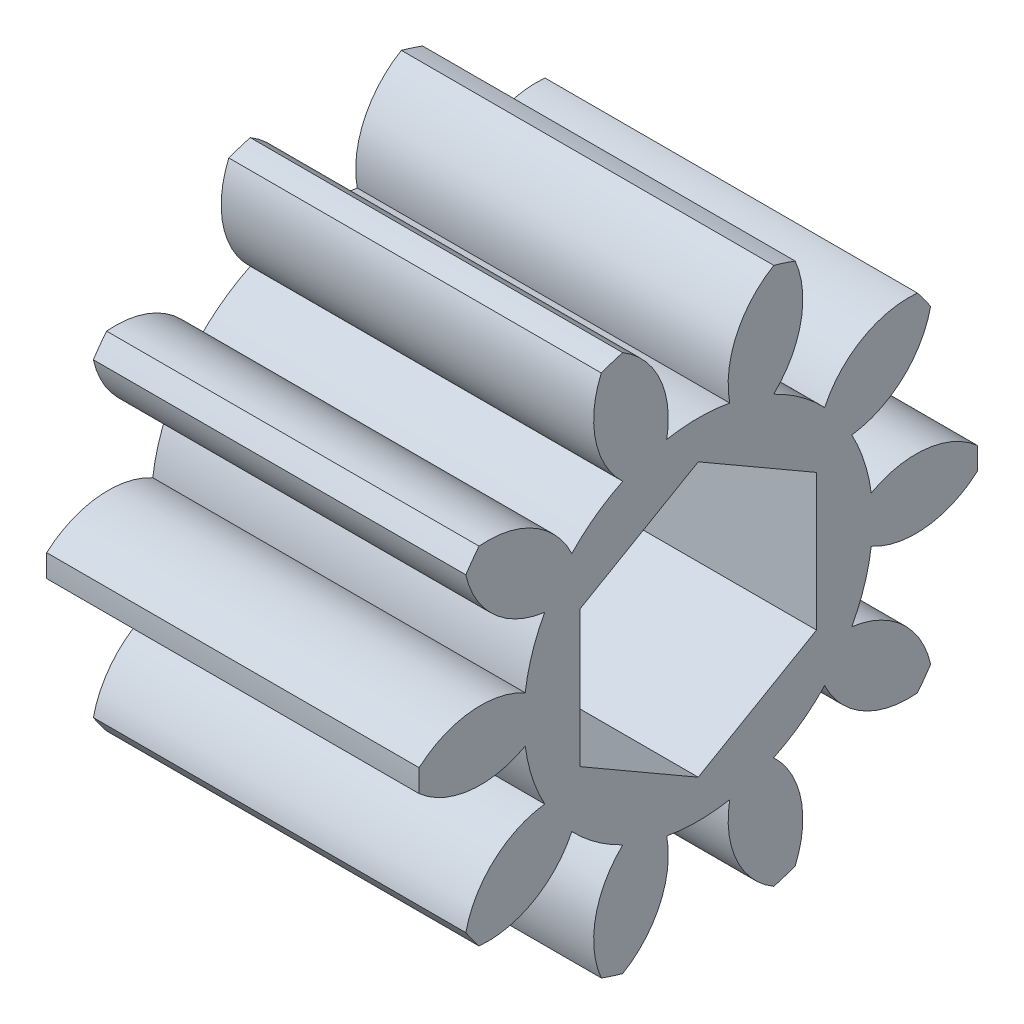
SolidWorks part; units mm, degrees
ref_plane "Plane1" through (0, 0, 0) normal (0, 0, 1) x (1, 0, 0)
ref_plane "Plane2" through (0, 0, 0) normal (0, 1, 0) x (1, 0, 0)
ref_plane "Plane3" through (0, 0, 0) normal (1, 0, 0) x (0, 0, -1)
other "Configuration Table"
sketch "HoldingSke" plane through (0, 0, 0) normal (0, 1, 0) x (1, 0, 0)
  line L0 (0, 0) -> (0.3939, -0.0695)
  line L1 (-15, 0) -> (100, 0) construction
  line L2 (0, 0) -> (-2.1039, 2.3779)
  line L3 (0, 0) -> (-11.863, 4.5341)
  line L4 (0, 0) -> (8.5048, 1.4996)
  line L5 (0, 0) -> (-46.8476, -17.4728)
  line L6 (0, 0) -> (-11.6055, -7.8303)
  line L7 (-2.1039, 2.3779) -> (8.6587, 51.2064)
  line L8 (-76.2, 54.61) -> (-74.4, 54.61)
  line L9 (-67.7845, 28.3722) -> (-49.3413, 33.142)
  line L10 (-76.2, 71.12) -> (104.1128, 71.12)
  line L11 (0, 0) -> (-14, 0)
  line L12 (-76.2, 101.6) -> (-76.113, 101.6)
  line L13 (24.9733, 27.94) -> (52.9518, 28.4284)
  line L14 (24.9733, 27.94) -> (24.9743, 27.94)
  line L15 (24.9733, 27.94) -> (100.4006, 29.5858)
  line L16 (-63.627, -2.5) -> (-12.827, -2.5)
  circle A0 centre (0, 0) radius 5
  circle A1 centre (0, 0) radius 9.374
  circle A2 centre (0, 0) radius 37.5
  circle A3 centre (0, 0) radius 5
  dimension "MHD" = 18.748
  dimension "Hub_dia" = 75
  dimension "Bore" = 10
  dimension "MBD" = 10
  dimension "Num_teeth" = 10
  dimension "Pitch" = 0.4
  dimension "Overall_len" = 50
  dimension "Show_teeth" = 10
  dimension "Thickness" = 14
  dimension "OAL" = 50.0006
  dimension "T_dim" = 1.8
  dimension "Ap" = 14.5
  dimension "H" = 19.05
  dimension "Pitch_radius" = 180.3128
  dimension "Width" = 14
  dimension "Backlash" = 0.087
  dimension "Addendum_fac" = 1
  dimension "Dedendum_fac" = 1.25
  dimension "Clearance_fac" = 0.25
  dimension "Dedendum_add" = 0.001
  dimension "Module" = 2.5
sketch "BasProSke" plane through (0, 0, 0) normal (0, 1, 0) x (1, 0, 0)
  line L0 (-10, 0) -> (60, 0) construction
  line L1 (0, 0) -> (0, 15)
  line L2 (0, 0) -> (14, 0)
  line L3 (14, 0) -> (14, 15)
  line L4 (14, 15) -> (0, 15)
  dimension "Thickness" = 14
  dimension "Diameter" = 30
revolve "Base-Revolve" add sketch "BasProSke" angle 360 about L0
sketch "TooCutSke" plane through (0, 0, 0) normal (1, 0, 0) x (0, 0, -1)
  line L1 (0, 0) -> (0, 107) construction
  line L2 (0, 0) -> (-2.1074, 12.3211) construction
  line L3 (0, 0) -> (-7.6446, 23.5277) construction
  line L4 (-2.1074, 12.3211) -> (-3.8223, 11.7639) construction
  arc A0 (1.6916, 9.2201) -> (-1.6916, 9.2201) centre (0, 0) ccw
  arc A1 (4.0875, 14.4587) -> (-4.0875, 14.4587) centre (0, 0) ccw
  circle A2 centre (0, 0) radius 12.5 construction
  circle A3 centre (0, 0) radius 12.1018 construction
  arc A4 (-1.6916, 9.2201) -> (-4.0875, 14.4587) centre (-6.6064, 10.1395) ccw
  arc A5 (4.0875, 14.4587) -> (1.6916, 9.2201) centre (6.6064, 10.1395) ccw
  dimension "Root_dia" = 18.748
  dimension "Overcut_dia" = 30.0508
  dimension "Pitch_dia" = 25
  dimension "Base_dia" = 24.2037
  dimension "Flank_rad" = 5
  dimension "Half_ang" = 18
  dimension "Half_CT" = 1.8032
extrude "ToothCut" cut sketch "TooCutSke" along normal through all
fillet "Breaks" [suppressed] radius 0.05
fillet "RootFillets" [suppressed] radius 0.626
pattern_circular "TeethCuts" count 10 every 36 about axis through (-10, 0, 0) along (1, 0, 0) of "ToothCut", "RootFillets", "Breaks"
sketch "HubNeaOneSke" plane through (0, 0, 0) normal (-1, 0, 0) x (0, 0, 1)
  circle A0 centre (0, 0) radius 9.374
  dimension "Diameter" = 18.748
extrude "HubNearOne" [suppressed] add sketch "HubNeaOneSke" along normal blind 36.0006
sketch "HubNeaBotSke" plane through (0, 0, 0) normal (-1, 0, 0) x (0, 0, 1)
  circle A0 centre (0, 0) radius 9.374
  dimension "Diameter" = 18.748
extrude "HubNearBoth" [suppressed] add sketch "HubNeaBotSke" along normal blind 18.0003
ref_plane "FarPln" through (14, 0, 0) normal (1, 0, 0) x (0, 0, -1)
sketch "HubFarSke" plane through (14, 0, 0) normal (1, 0, 0) x (0, 0, -1)
  circle A0 centre (0, 0) radius 9.374
  dimension "Diameter" = 18.748
extrude "HubFar" [suppressed] add sketch "HubFarSke" along normal blind 18.0003
sketch "BorSke" plane through (0, 0, 0) normal (1, 0, 0) x (0, 0, -1)
  circle A0 centre (0, 0) radius 5
  dimension "Diameter" = 10
extrude "Bore" cut sketch "BorSke" along normal mid plane 100.0011
sketch "KeySke" plane through (0, 0, 0) normal (1, 0, 0) x (0, 0, -1)
  line L0 (-2, 0) -> (-2, 6.8)
  line L1 (-2, 6.8) -> (2, 6.8)
  line L2 (2, 6.8) -> (2, 0)
  line L3 (0, 0) -> (0, 34) construction
  line L4 (-2, 0) -> (2, 0)
  dimension "Offset" = 6.8
  dimension "Width" = 4
extrude "Keyway" [suppressed] cut sketch "KeySke" along normal mid plane 100.0011
pattern_circular "Keyway2" [suppressed] count 2 every 90 about axis through (-10, 0, 0) along (1, 0, 0)
sketch "Sketch1" plane through (14, 0, 0) normal (1, 0, 0) x (0, 0, -1)
  line L1 (0, -7.3323) -> (6.35, -3.6662)
  line L2 (6.35, -3.6662) -> (6.35, 3.6662)
  line L3 (6.35, 3.6662) -> (0, 7.3323)
  line L4 (0, 7.3323) -> (-6.35, 3.6662)
  line L5 (-6.35, 3.6662) -> (-6.35, -3.6662)
  line L6 (-6.35, -3.6662) -> (0, -7.3323)
  circle A0 centre (0, 0) radius 6.35 construction
  point P1 (2.938, 6.4082)
  point P9 (0, 0)
  point P10 (0, 0)
  point P12 (0, 7.5633)
  dimension "D1" = 12.7
extrude "Cut-Extrude1" cut sketch "Sketch1" against normal through all
sketch "Sketch2" plane through (14, 0, 0) normal (1, 0, 0) x (0, 0, -1)
  line L0 (-6.35, -3.6662) -> (0, -7.3323)
  line L1 (-6.35, -3.6662) -> (0, -7.3323)
  line L2 (0, -7.3323) -> (6.35, -3.6662)
  line L3 (0, -7.3323) -> (6.35, -3.6662)
  line L4 (6.35, -3.6662) -> (6.35, 3.6662)
  line L5 (6.35, -3.6662) -> (6.35, 3.6662)
  line L6 (6.35, 3.6662) -> (0, 7.3323)
  line L7 (6.35, 3.6662) -> (0, 7.3323)
  line L8 (0, 7.3323) -> (-6.35, 3.6662)
  line L9 (0, 7.3323) -> (-6.35, 3.6662)
  line L10 (-6.35, 3.6662) -> (-6.35, -3.6662)
  line L11 (-6.35, 3.6662) -> (-6.35, -3.6662)
  arc A0 (14.9878, -0.6039) -> (14.9878, 0.6039) centre (0, 0) ccw
  arc A1 (14.9878, -0.6039) -> (14.9878, 0.6039) centre (0, 0) ccw
  arc A2 (9.2916, -1.2403) -> (14.9878, -0.6039) centre (11.6848, 3.1497) ccw
  arc A3 (9.2916, -1.2403) -> (14.9878, -0.6039) centre (11.6848, 3.1497) ccw
  arc A4 (8.2461, -4.458) -> (9.2916, -1.2403) centre (0, 0) ccw
  arc A5 (8.2461, -4.458) -> (9.2916, -1.2403) centre (0, 0) ccw
  arc A6 (12.4804, -8.3211) -> (8.2461, -4.458) centre (7.6018, -9.4163) ccw
  arc A7 (12.4804, -8.3211) -> (8.2461, -4.458) centre (7.6018, -9.4163) ccw
  arc A8 (11.7705, -9.2982) -> (12.4804, -8.3211) centre (0, 0) ccw
  arc A9 (11.7705, -9.2982) -> (12.4804, -8.3211) centre (0, 0) ccw
  arc A10 (6.788, -6.4649) -> (11.7705, -9.2982) centre (11.3045, -4.3199) ccw
  arc A11 (6.788, -6.4649) -> (11.7705, -9.2982) centre (11.3045, -4.3199) ccw
  arc A12 (4.0509, -8.4535) -> (6.788, -6.4649) centre (0, 0) ccw
  arc A13 (4.0509, -8.4535) -> (6.788, -6.4649) centre (0, 0) ccw
  arc A14 (5.2058, -14.0677) -> (4.0509, -8.4535) centre (0.6152, -12.0862) ccw
  arc A15 (5.2058, -14.0677) -> (4.0509, -8.4535) centre (0.6152, -12.0862) ccw
  arc A16 (4.0572, -14.4409) -> (5.2058, -14.0677) centre (0, 0) ccw
  arc A17 (4.0572, -14.4409) -> (5.2058, -14.0677) centre (0, 0) ccw
  arc A18 (1.6916, -9.2201) -> (4.0572, -14.4409) centre (6.6064, -10.1395) ccw
  arc A19 (1.6916, -9.2201) -> (4.0572, -14.4409) centre (6.6064, -10.1395) ccw
  arc A20 (-1.6916, -9.2201) -> (1.6916, -9.2201) centre (0, 0) ccw
  arc A21 (-1.6916, -9.2201) -> (1.6916, -9.2201) centre (0, 0) ccw
  arc A22 (-4.0572, -14.4409) -> (-1.6916, -9.2201) centre (-6.6064, -10.1395) ccw
  arc A23 (-4.0572, -14.4409) -> (-1.6916, -9.2201) centre (-6.6064, -10.1395) ccw
  arc A24 (-5.2058, -14.0677) -> (-4.0572, -14.4409) centre (0, 0) ccw
  arc A25 (-5.2058, -14.0677) -> (-4.0572, -14.4409) centre (0, 0) ccw
  arc A26 (-4.0509, -8.4535) -> (-5.2058, -14.0677) centre (-0.6152, -12.0862) ccw
  arc A27 (-4.0509, -8.4535) -> (-5.2058, -14.0677) centre (-0.6152, -12.0862) ccw
  arc A28 (-6.788, -6.4649) -> (-4.0509, -8.4535) centre (0, 0) ccw
  arc A29 (-6.788, -6.4649) -> (-4.0509, -8.4535) centre (0, 0) ccw
  arc A30 (-11.7705, -9.2982) -> (-6.788, -6.4649) centre (-11.3045, -4.3199) ccw
  arc A31 (-11.7705, -9.2982) -> (-6.788, -6.4649) centre (-11.3045, -4.3199) ccw
  arc A32 (-12.4804, -8.3211) -> (-11.7705, -9.2982) centre (0, 0) ccw
  arc A33 (-12.4804, -8.3211) -> (-11.7705, -9.2982) centre (0, 0) ccw
  arc A34 (-8.2461, -4.458) -> (-12.4804, -8.3211) centre (-7.6018, -9.4163) ccw
  arc A35 (-8.2461, -4.458) -> (-12.4804, -8.3211) centre (-7.6018, -9.4163) ccw
  arc A36 (-9.2916, -1.2403) -> (-8.2461, -4.458) centre (0, 0) ccw
  arc A37 (-9.2916, -1.2403) -> (-8.2461, -4.458) centre (0, 0) ccw
  arc A38 (-14.9878, -0.6039) -> (-9.2916, -1.2403) centre (-11.6848, 3.1497) ccw
  arc A39 (-14.9878, -0.6039) -> (-9.2916, -1.2403) centre (-11.6848, 3.1497) ccw
  arc A40 (-14.9878, 0.6039) -> (-14.9878, -0.6039) centre (0, 0) ccw
  arc A41 (-14.9878, 0.6039) -> (-14.9878, -0.6039) centre (0, 0) ccw
  arc A42 (-9.2916, 1.2403) -> (-14.9878, 0.6039) centre (-11.6848, -3.1497) ccw
  arc A43 (-9.2916, 1.2403) -> (-14.9878, 0.6039) centre (-11.6848, -3.1497) ccw
  arc A44 (-8.2461, 4.458) -> (-9.2916, 1.2403) centre (0, 0) ccw
  arc A45 (-8.2461, 4.458) -> (-9.2916, 1.2403) centre (0, 0) ccw
  arc A46 (-12.4804, 8.3211) -> (-8.2461, 4.458) centre (-7.6018, 9.4163) ccw
  arc A47 (-12.4804, 8.3211) -> (-8.2461, 4.458) centre (-7.6018, 9.4163) ccw
  arc A48 (-11.7705, 9.2982) -> (-12.4804, 8.3211) centre (0, 0) ccw
  arc A49 (-11.7705, 9.2982) -> (-12.4804, 8.3211) centre (0, 0) ccw
  arc A50 (-6.788, 6.4649) -> (-11.7705, 9.2982) centre (-11.3045, 4.3199) ccw
  arc A51 (-6.788, 6.4649) -> (-11.7705, 9.2982) centre (-11.3045, 4.3199) ccw
  arc A52 (-4.0509, 8.4535) -> (-6.788, 6.4649) centre (0, 0) ccw
  arc A53 (-4.0509, 8.4535) -> (-6.788, 6.4649) centre (0, 0) ccw
  arc A54 (-5.2058, 14.0677) -> (-4.0509, 8.4535) centre (-0.6152, 12.0862) ccw
  arc A55 (-5.2058, 14.0677) -> (-4.0509, 8.4535) centre (-0.6152, 12.0862) ccw
  arc A56 (-4.0572, 14.4409) -> (-5.2058, 14.0677) centre (0, 0) ccw
  arc A57 (-4.0572, 14.4409) -> (-5.2058, 14.0677) centre (0, 0) ccw
  arc A58 (-1.6916, 9.2201) -> (-4.0572, 14.4409) centre (-6.6064, 10.1395) ccw
  arc A59 (-1.6916, 9.2201) -> (-4.0572, 14.4409) centre (-6.6064, 10.1395) ccw
  arc A60 (1.6916, 9.2201) -> (-1.6916, 9.2201) centre (0, 0) ccw
  arc A61 (1.6916, 9.2201) -> (-1.6916, 9.2201) centre (0, 0) ccw
  arc A62 (4.0572, 14.4409) -> (1.6916, 9.2201) centre (6.6064, 10.1395) ccw
  arc A63 (4.0572, 14.4409) -> (1.6916, 9.2201) centre (6.6064, 10.1395) ccw
  arc A64 (5.2058, 14.0677) -> (4.0572, 14.4409) centre (0, 0) ccw
  arc A65 (5.2058, 14.0677) -> (4.0572, 14.4409) centre (0, 0) ccw
  arc A66 (4.0509, 8.4535) -> (5.2058, 14.0677) centre (0.6152, 12.0862) ccw
  arc A67 (4.0509, 8.4535) -> (5.2058, 14.0677) centre (0.6152, 12.0862) ccw
  arc A68 (6.788, 6.4649) -> (4.0509, 8.4535) centre (0, 0) ccw
  arc A69 (6.788, 6.4649) -> (4.0509, 8.4535) centre (0, 0) ccw
  arc A70 (11.7705, 9.2982) -> (6.788, 6.4649) centre (11.3045, 4.3199) ccw
  arc A71 (11.7705, 9.2982) -> (6.788, 6.4649) centre (11.3045, 4.3199) ccw
  arc A72 (12.4804, 8.3211) -> (11.7705, 9.2982) centre (0, 0) ccw
  arc A73 (12.4804, 8.3211) -> (11.7705, 9.2982) centre (0, 0) ccw
  arc A74 (8.2461, 4.458) -> (12.4804, 8.3211) centre (7.6018, 9.4163) ccw
  arc A75 (8.2461, 4.458) -> (12.4804, 8.3211) centre (7.6018, 9.4163) ccw
  arc A76 (9.2916, 1.2403) -> (8.2461, 4.458) centre (0, 0) ccw
  arc A77 (9.2916, 1.2403) -> (8.2461, 4.458) centre (0, 0) ccw
  arc A78 (14.9878, 0.6039) -> (9.2916, 1.2403) centre (11.6848, -3.1497) ccw
  arc A79 (14.9878, 0.6039) -> (9.2916, 1.2403) centre (11.6848, -3.1497) ccw
extrude "Boss-Extrude1" add sketch "Sketch2" along normal blind 6
equation "' \"Module@HoldingSke\" = 6.35"
equation "' \"Num_teeth@HoldingSke\" = 12"
equation "' \"Ap@HoldingSke\" =  20"
equation "' \"Ap@HoldingSke\" = 20"
equation "' \"Width@HoldingSke\" = 0.5 * 25.4"
equation "' \"Hub_dia@HoldingSke\"= 1 * 25.4"
equation "' \"Hub_dia@HoldingSke\" = 1 * 25.4"
equation "' \"Overall_len@HoldingSke\" = 1.0 * 25.4"
equation "' \"Bore@HoldingSke\" = 0.75 * 25.4"
equation "' \"T_dim@HoldingSke\" = 0.1 * 25.4"
equation "' \"Width@KeySke\" = 0.25 * 25.4"
equation "' \"Show_teeth@HoldingSke\" = 13"
equation "' \"Backlash@HoldingSke\" = 0.009 * 25.4"
equation "' \"Addendum_fac@HoldingSke\" = 1.0"
equation "' \"Dedendum_fac@HoldingSke\" = 1.25"
equation "' \"Dedendum_add@HoldingSke\" = 0.00005 * 25.4"
equation "' \"Clearance_fac@HoldingSke\" = 0.25"
equation "\"Pitch@HoldingSke\" = 1 / \"Module@HoldingSke\""
equation "\"Overcut_dia@TooCutSke\" = (\"Num_teeth@HoldingSke\" + 2 * \"Addendum_fac@HoldingSke\") / \"Pitch@HoldingSke\" + 0.002 * 25.4"
equation "\"Pitch_dia@TooCutSke\" = \"Num_teeth@HoldingSke\" / \"Pitch@HoldingSke\""
equation "\"Base_dia@TooCutSke\" = \"Num_teeth@HoldingSke\" / \"Pitch@HoldingSke\" * cos((\"Ap@HoldingSke\"  * 3.14159265 / 180))"
equation "\"Root_dia@TooCutSke\" = (\"Num_teeth@HoldingSke\" + 2) / \"Pitch@HoldingSke\" - 2 * (\"Addendum_fac@HoldingSke\" + \"Dedendum_fac@HoldingSke\") / \"Pitch@HoldingSke\" - \"Dedendum_add@HoldingSke\" * 2"
equation "\"Half_ang@TooCutSke\" = 180 / \"Num_teeth@HoldingSke\""
equation "\"Half_CT@TooCutSke\" = \"Num_teeth@HoldingSke\" / \"Pitch@HoldingSke\" * sin((3.14159265 / 2 / \"Num_teeth@HoldingSke\")) / 2 - 7 * \"Backlash@HoldingSke\" / 4"
equation "\"Flank_rad@TooCutSke\" = \"Num_teeth@HoldingSke\" / \"Pitch@HoldingSke\" / 5"
equation "\"Radius@RootFillets\" = \"Clearance_fac@HoldingSke\" / \"Pitch@HoldingSke\" + \"Dedendum_add@HoldingSke\""
equation "\"Break_rad@Breaks\" = 0.02 / \"Pitch@HoldingSke\""
equation "\"Thickness@HoldingSke\" = \"Width@HoldingSke\""
equation "\"OAL@HoldingSke\" = \"Thickness@HoldingSke\""
equation "\"MHD@HoldingSke\" = (\"Num_teeth@HoldingSke\" + 2) / \"Pitch@HoldingSke\" - 2 * (\"Addendum_fac@HoldingSke\" + \"Dedendum_fac@HoldingSke\")  / \"Pitch@HoldingSke\" - \"Dedendum_add@HoldingSke\" * 2"
equation "\"MBD@HoldingSke\" = (\"Num_teeth@HoldingSke\" + 2) / \"Pitch@HoldingSke\" - 2 * (\"Addendum_fac@HoldingSke\" + \"Dedendum_fac@HoldingSke\")  / \"Pitch@HoldingSke\" - \"Dedendum_add@HoldingSke\" * 2 - 0.002 * 25.4"
equation "\"MHD@HoldingSke\" = ((sgn( \"MHD@HoldingSke\" - \"Hub_dia@HoldingSke\" )-1)*( \"MHD@HoldingSke\" - \"Hub_dia@HoldingSke\" ))/-2+ \"Hub_dia@HoldingSke\""
equation "\"MBD@HoldingSke\" = ((sgn( \"MBD@HoldingSke\" - \"Bore@HoldingSke\" )-1)*( \"MBD@HoldingSke\" - \"Bore@HoldingSke\" ))/-2+ \"Bore@HoldingSke\""
equation "\"OAL@HoldingSke\" = ((sgn( \"OAL@HoldingSke\" - \"Overall_len@HoldingSke\" )+1)*( \"OAL@HoldingSke\" - \"Overall_len@HoldingSke\" ))/2 + \"Overall_len@HoldingSke\" + 0.000002 * 25.4"
equation "\"Num_teeth@TeethCuts\" = int( \"Show_teeth@HoldingSke\" ) + 1"
equation "\"Num_teeth@TeethCuts\" = ((sgn( \"Num_teeth@TeethCuts\" - \"Num_teeth@HoldingSke\" )-1)*( \"Num_teeth@TeethCuts\" - \"Num_teeth@HoldingSke\" ))/-2+ \"Num_teeth@HoldingSke\""
equation "\"Num_teeth@TeethCuts\" = ((sgn( \"Num_teeth@TeethCuts\" - 2.0)+1)*( \"Num_teeth@TeethCuts\" - 2.0))/2 +2.0"
equation "\"Angle@TeethCuts\" = 360.0 / \"Num_teeth@HoldingSke\""
equation "\"Diameter@BasProSke\" = (\"Num_teeth@HoldingSke\" + 2 * \"Addendum_fac@HoldingSke\") / \"Pitch@HoldingSke\""
equation "\"Thickness@BasProSke\"  = \"Thickness@HoldingSke\""
equation "' \"Fillet_rad@BasProSke\" =  \"Thickness@HoldingSke\" * 0.05"
equation "' \"Fillet_rad@BasProSke\" = \"Thickness@HoldingSke\" * 0.05"
equation "\"MHD@HoldingSke\" = ((sgn( \"MHD@HoldingSke\" - \"Root_dia@TooCutSke\" )-1)*( \"MHD@HoldingSke\" - \"Root_dia@TooCutSke\" ))/-2+ \"Root_dia@TooCutSke\""
equation "\"Diameter@HubNeaOneSke\" = \"MHD@HoldingSke\""
equation "\"Length@HubNearOne\" = \"OAL@HoldingSke\" - \"Thickness@BasProSke\""
equation "\"Diameter@HubNeaBotSke\" = \"MHD@HoldingSke\""
equation "\"Length@HubNearBoth\" = ( \"OAL@HoldingSke\" - \"Thickness@BasProSke\" ) / 2.0"
equation "\"Thickness@FarPln\" = \"Thickness@BasProSke\""
equation "\"Diameter@HubFarSke\" = \"MHD@HoldingSke\""
equation "\"Length@HubFar\" = ( \"OAL@HoldingSke\" - \"Thickness@BasProSke\" ) / 2.0"
equation "\"Diameter@BorSke\" = \"MBD@HoldingSke\""
equation "\"D1@Bore\" = \"OAL@HoldingSke\" * 2.0"
equation "\"D1@Keyway\" = \"OAL@HoldingSke\" * 2.0"
equation "\"Offset@KeySke\" = \"T_dim@HoldingSke\" + \"MBD@HoldingSke\" / 2.0"
